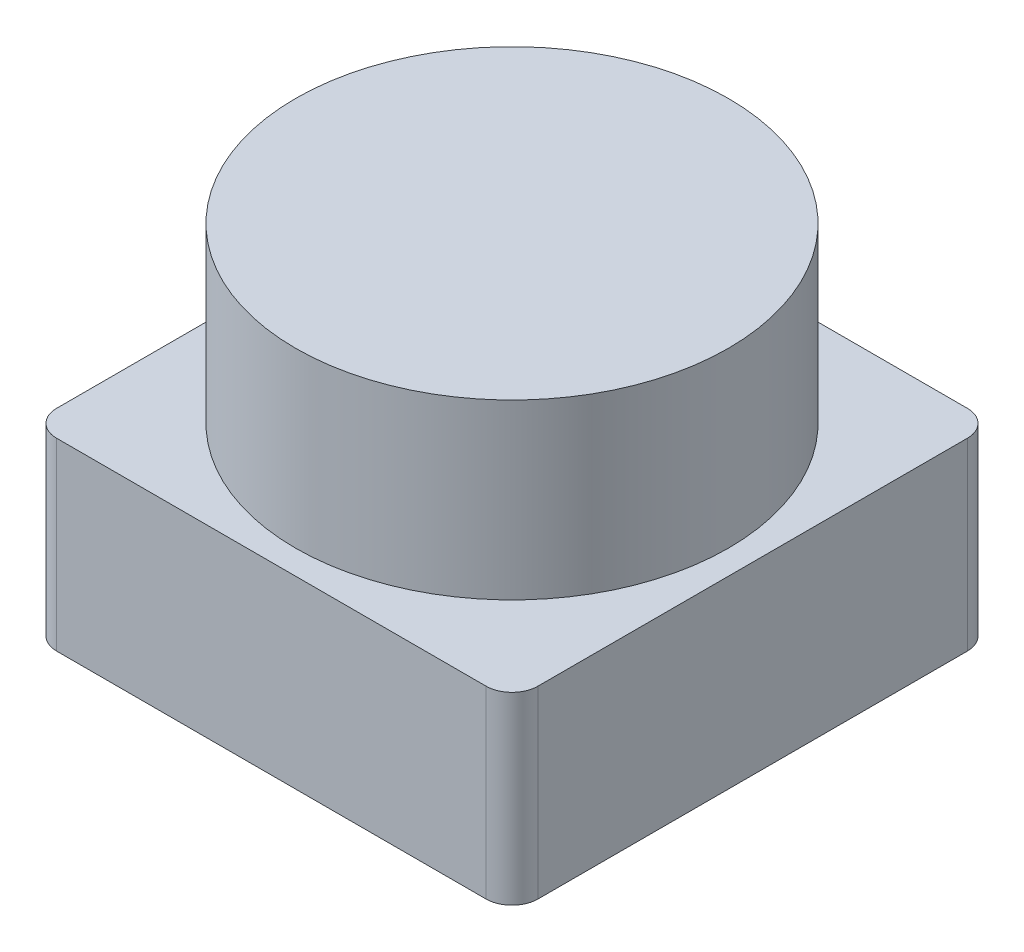
SolidWorks part; units mm, degrees
material "Hexcel AS4C (3000 丝)"
ref_plane "前视基准面" through (0, 0, 0) normal (0, 0, 1) x (1, 0, 0)
ref_plane "上视基准面" through (0, 0, 0) normal (0, 1, 0) x (1, 0, 0)
ref_plane "右视基准面" through (0, 0, 0) normal (1, 0, 0) x (0, 0, -1)
sketch "草图1" plane through (0, 0, 0) normal (0, 1, 0) x (1, 0, 0)
  line L1 (0, 0) -> (55.6, 0)
  line L2 (0, 0) -> (0, 55.6)
  line L3 (0, 55.6) -> (55.6, 55.6)
  line L4 (55.6, 0) -> (55.6, 55.6)
  dimension "D1" = 55.6
  dimension "D2" = 55.6
extrude "凸台-拉伸1" add sketch "草图1" along normal blind 21.3
sketch "草图2" plane through (0, 21.3, 0) normal (0, 1, 0) x (1, 0, 0)
  line L0 (0, 55.6) -> (55.6, 0)
  circle A0 centre (27.8, 27.8) radius 25
  dimension "D1" = 50
extrude "凸台-拉伸2" add sketch "草图2" along normal blind 20 contours L0 A0 | L0 A0
fillet "圆角1" radius 3 4 edges at (0, 10.65, -55.6) (55.6, 10.65, -55.6) (55.6, 10.65, 0) (0, 10.65, 0)
sketch "草图3" plane through (0, 0, 0) normal (0, -1, 0) x (1, 0, 0)
  line L0 (0, -27.8) -> (55.6, -27.8)
  line L1 (0, -52.6) -> (0, -3) construction
  line L2 (55.6, -3) -> (55.6, -52.6) construction
  line L4 (6.3, -49.3) -> (49.3, -49.3)
  line L5 (6.3, -49.3) -> (6.3, -6.3)
  line L6 (6.3, -6.3) -> (49.3, -6.3)
  line L7 (49.3, -49.3) -> (49.3, -6.3)
  line L8 (6.3, -49.3) -> (49.3, -6.3) construction
  line L9 (6.3, -6.3) -> (49.3, -49.3) construction
  point P6 (27.8, -27.8)
  dimension "D1" = 43
  dimension "D2" = 43
sketch "草图4" plane through (0, 0, 0) normal (0, -1, 0) x (-1, 0, 0)
  point P0 (-49.3, 49.3)
  point P3 (-6.3, 49.3)
  point P6 (-6.3, 6.3)
  point P9 (-49.3, 6.3)
hole_wizard "孔1" positions "草图4" profile "草图5" legacy
sketch "草图5" plane through (49.3, 0, -49.3) normal (1, 0, 0) x (0, 0, -1)
  line L0 (0, 0) -> (0, 4)
  line L1 (0, 4) -> (1.5, 4)
  line L2 (1.5, 4) -> (1.5, 0)
  line L3 (1.5, 0) -> (0, 0)
  line L4 (0, 110) -> (0, -10) construction
  dimension "直径" = 3
  dimension "深度" = 4
